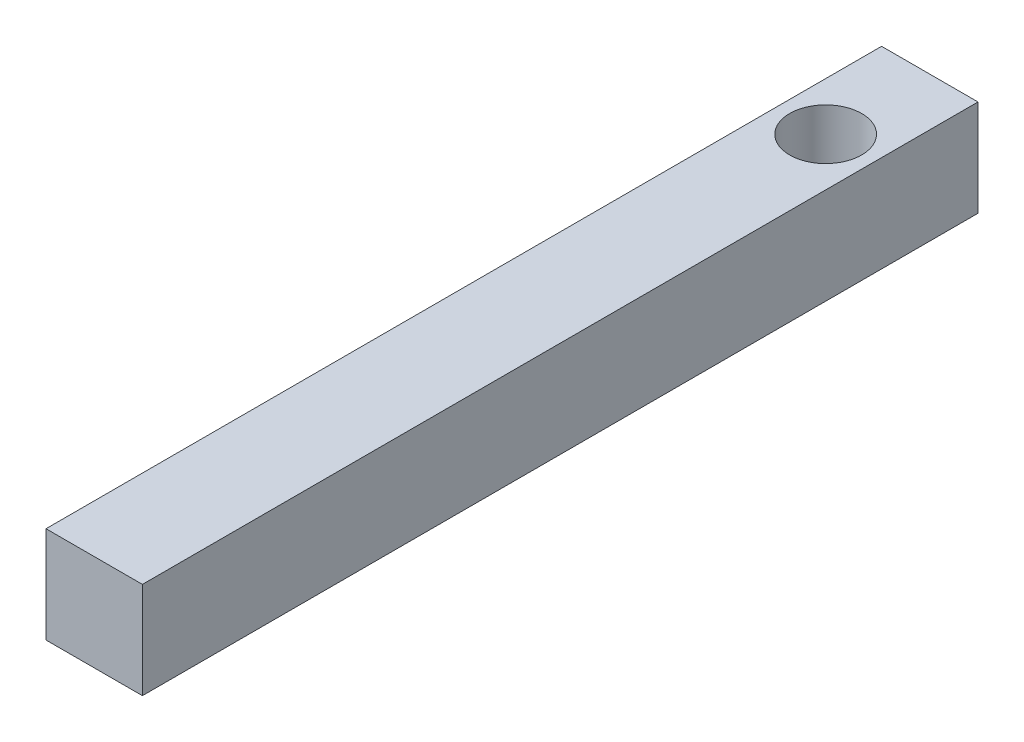
SolidWorks part; units mm, degrees
ref_plane "前视基准面" through (0, 0, 0) normal (0, 0, 1) x (1, 0, 0)
ref_plane "上视基准面" through (0, 0, 0) normal (0, 1, 0) x (1, 0, 0)
ref_plane "右视基准面" through (0, 0, 0) normal (1, 0, 0) x (0, 0, -1)
sketch "草图2" plane through (0, 0, 0) normal (0, 0, 1) x (1, 0, 0)
  line L1 (0, 0) -> (19.05, 0)
  line L2 (0, 0) -> (0, 19.05)
  line L3 (0, 19.05) -> (19.05, 19.05)
  line L4 (19.05, 0) -> (19.05, 19.05)
extrude "凸台-拉伸1" add sketch "草图2" along normal blind 165.1
ref_plane "基准面1" through (0, 19.05, 0) normal (0, 1, 0) x (1, 0, 0)
sketch "草图3" plane through (0, 19.05, 0) normal (0, 1, 0) x (1, 0, 0)
  line L0 (9.525, 0) -> (9.525, -20.574) construction
  line L1 (19.05, 0) -> (0, 0) construction
  circle A0 centre (9.525, -20.574) radius 7.112
extrude "切除-拉伸1" cut sketch "草图3" against normal through all
